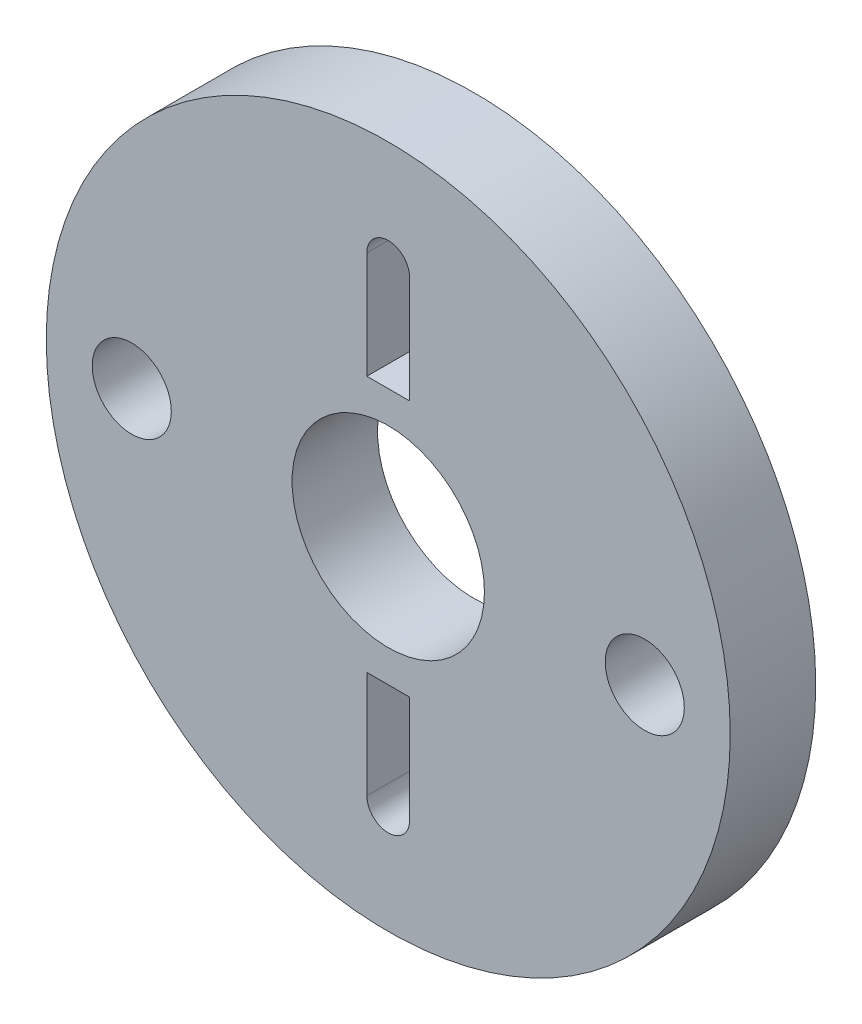
SolidWorks part; units mm, degrees
ref_plane "前视基准面" through (0, 0, 0) normal (0, 0, 1) x (1, 0, 0)
ref_plane "上视基准面" through (0, 0, 0) normal (0, 1, 0) x (1, 0, 0)
ref_plane "右视基准面" through (0, 0, 0) normal (1, 0, 0) x (0, 0, -1)
sketch "草图1" plane through (0, 0, 0) normal (0, 0, 1) x (1, 0, 0)
  line L2 (0, -55) -> (0, 55) construction
  line L3 (55, 0) -> (-55, 0) construction
  line L4 (0, 6) -> (0, 11) construction
  line L5 (-1, 6) -> (-1, 11)
  line L6 (1, 6) -> (1, 11)
  line L7 (0, -6) -> (0, -11) construction
  line L8 (1, -6) -> (1, -11)
  line L9 (-1, -6) -> (-1, -11)
  line L10 (-1, -6) -> (1, -6)
  line L11 (1, 6) -> (-1, 6)
  circle A0 centre (0, 0) radius 16
  circle A1 centre (0, 0) radius 4.5
  arc A3 (1, 11) -> (-1, 11) centre (0, 11) ccw
  arc A5 (-1, -11) -> (1, -11) centre (0, -11) ccw
  circle A6 centre (-12, 0) radius 1.85
  circle A7 centre (12, 0) radius 1.85
  point P2 (0, 6)
  point P3 (0, 11)
  point P8 (12, 0)
  point P9 (-12, 0)
  point P12 (0, -6)
  point P13 (0, -11)
  point P14 (-6, 0)
  point P15 (-12, 0)
  point P16 (0, 8.5)
  point P23 (0, -8.5)
extrude "凸台-拉伸1" add sketch "草图1" along normal mid plane 4
